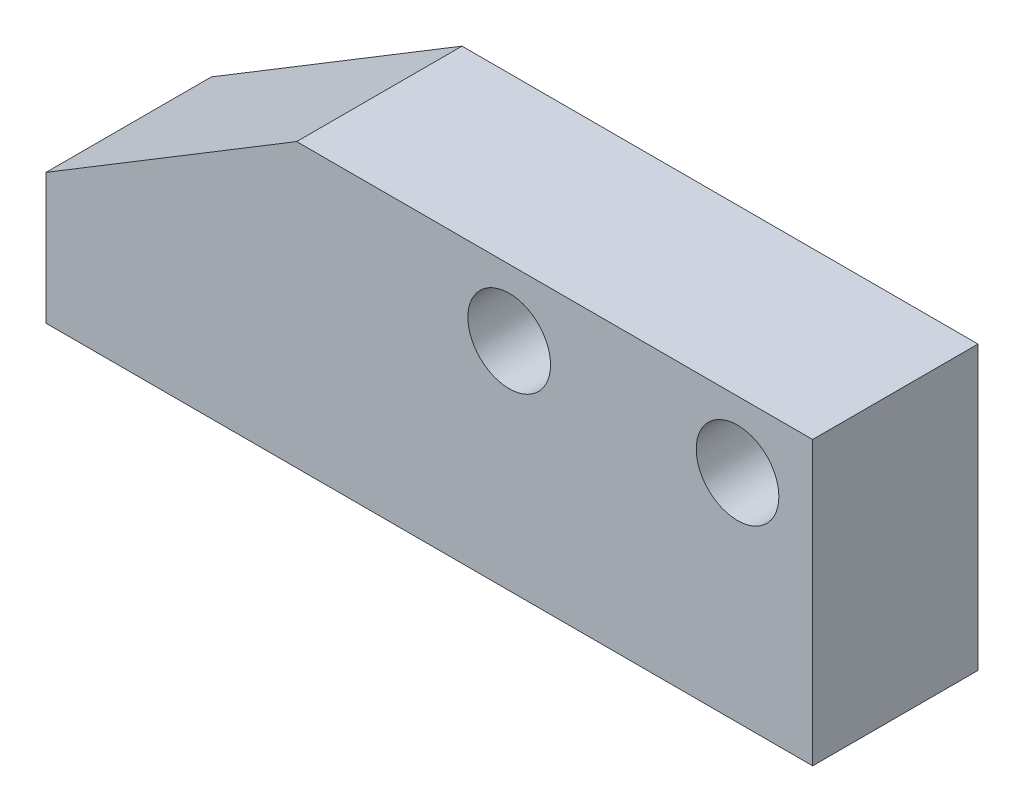
SolidWorks part; units mm, degrees
ref_plane "Front Plane" through (0, 0, 0) normal (0, 0, 1) x (1, 0, 0)
ref_plane "Top Plane" through (0, 0, 0) normal (0, 1, 0) x (1, 0, 0)
ref_plane "Right Plane" through (0, 0, 0) normal (1, 0, 0) x (0, 0, -1)
sketch "Sketch1" plane through (0, 0, 0) normal (0, 0, 1) x (1, 0, 0)
  line L0 (-76.4516, 87.5806) -> (110.8065, 87.5806)
  line L1 (110.8065, 87.5806) -> (110.8065, -15)
  line L2 (110.8065, -15) -> (-167.4194, -15)
  line L3 (-167.4194, -15) -> (-167.4194, 32.4194)
  line L4 (-167.4194, 32.4194) -> (-76.4516, 87.5806)
  circle A0 centre (83.5387, 63.4745) radius 15
  circle A1 centre (0.6747, 63.4745) radius 15
  point P6 (0, 0)
  dimension "D1" = 30
  dimension "D2" = 30
extrude "Boss-Extrude1" add sketch "Sketch1" along normal blind 60
